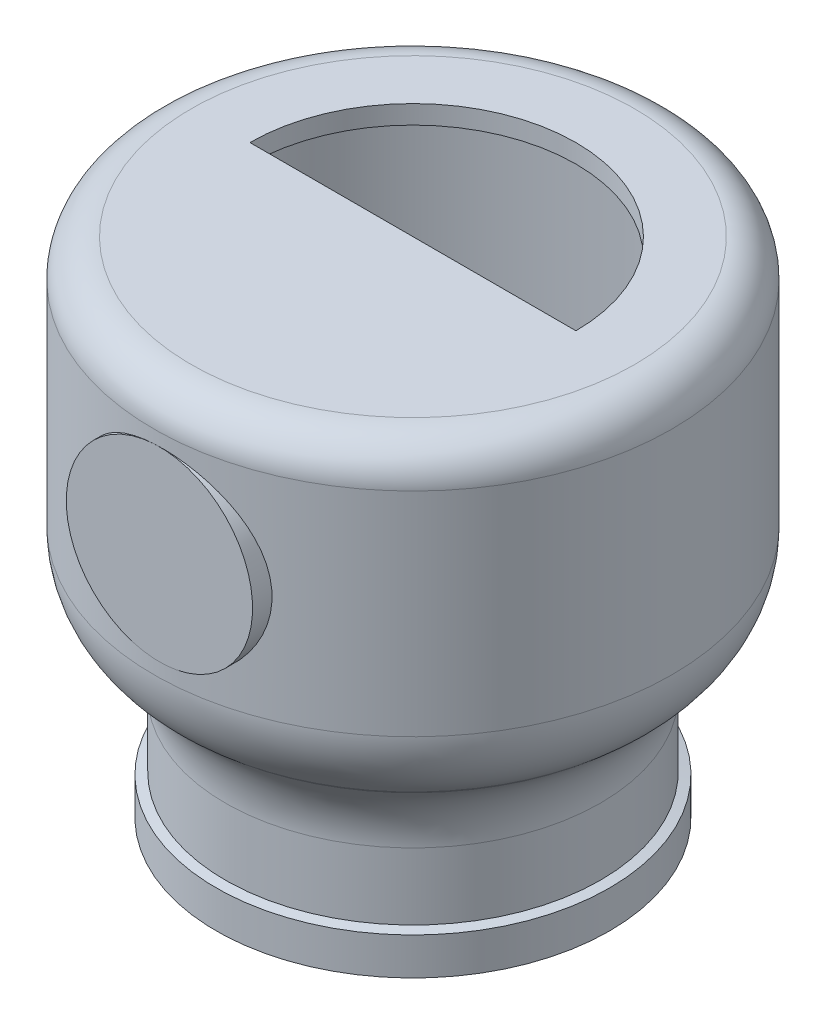
SolidWorks part; units mm, degrees
ref_plane "Front Plane" through (0, 0, 0) normal (0, 0, 1) x (1, 0, 0)
ref_plane "Top Plane" through (0, 0, 0) normal (0, 1, 0) x (1, 0, 0)
ref_plane "Right Plane" through (0, 0, 0) normal (1, 0, 0) x (0, 0, -1)
sketch "Sketch1" plane through (0, 0, 0) normal (0, 0, 1) x (1, 0, 0)
  line L0 (2.7649, 7.8218) -> (2.7649, 58.3592) construction
  line L1 (20.9, 0) -> (23.8716, 0)
  line L2 (23.8716, 0) -> (23.8716, 4)
  line L3 (23.8716, 4) -> (22.9, 4.2367)
  line L4 (22.9, 4.2367) -> (22.9, 11.4043)
  line L6 (20.9, 0) -> (20.9, 14)
  line L8 (2.7649, 52) -> (2.7649, 54)
  line L10 (17.2603, 17) -> (2.7649, 17)
  line L12 (19.9, 15) -> (2.7649, 15)
  line L13 (2.7649, 17) -> (2.7649, 15)
  line L15 (23.6882, 19.3396) -> (24.9883, 20.4305)
  line L16 (28.5604, 28.091) -> (28.5604, 50)
  line L17 (26.4721, 19.0648) -> (26.9883, 19.4979)
  line L18 (30.5604, 27.1583) -> (30.5604, 50)
  line L19 (26.5604, 52) -> (2.7649, 52)
  line L20 (26.5604, 54) -> (2.7649, 54)
  arc A0 (28.5604, 50) -> (26.5604, 52) centre (26.5604, 50) ccw
  arc A1 (30.5604, 50) -> (26.5604, 54) centre (26.5604, 50) ccw
  arc A2 (26.4721, 19.0648) -> (22.9, 11.4043) centre (32.9, 11.4043) ccw
  arc A3 (26.9883, 19.4979) -> (30.5604, 27.1583) centre (20.5604, 27.1583) ccw
  arc A4 (24.9883, 20.4305) -> (28.5604, 28.091) centre (18.5604, 28.091) ccw
  arc A5 (17.2603, 17) -> (23.6882, 19.3396) centre (17.2603, 27) ccw
  arc A6 (20.9, 14) -> (19.9, 15) centre (19.9, 14) ccw
  point P11 (22.9, 54)
  point P28 (28.5604, 23.4279)
  point P31 (20.9, 17)
  dimension "D8" = 2
  dimension "D9" = 4
  dimension "D4" = 2
  dimension "D16" = 10
  dimension "D17" = 10
  dimension "D18" = 10
  dimension "D19" = 1
  dimension "D1" = 2
  dimension "D2" = 4
  dimension "D3" = 1
  dimension "D5" = 140
  dimension "D6" = 2
  dimension "D7" = 2.9716
  dimension "D10" = 2
  dimension "D11" = 15
  dimension "D12" = 35
  dimension "D13" = 37
  dimension "D14" = 2
  dimension "D15" = 10
revolve "Revolve1" add sketch "Sketch1" angle 360 about L0
ref_plane "Plane1" through (0, 4, 0) normal (0, 1, 0) x (1, 0, 0)
sketch "Sketch3" plane through (0, 0, 0) normal (0, 0, 1) x (1, 0, 0)
  point P0 (1.2404, 19.1989)
ref_point "Point1"
ref_plane "Plane2" through (0, 0, 22.9) normal (0, 0, 1) x (1, 0, 0)
ref_plane "Plane3" through (0, 0, 27.7955) normal (0, 0, 1) x (1, 0, 0)
ref_plane "Plane4" through (0, 54, 0) normal (0, 1, 0) x (1, 0, 0)
sketch "Sketch9" plane through (0, 54, 0) normal (0, 1, 0) x (1, 0, 0)
  line L0 (-14.7351, -0.0013) -> (20.2649, -0.0013)
  arc A0 (20.2649, -0.0013) -> (-14.7351, -0.0013) centre (2.7649, -0.0013) ccw
  circle A1 centre (2.7649, 0) radius 17.1351 construction
  dimension "D1" = 35
  dimension "D3" = 17.5
  dimension "D2" = 17.5
extrude "Cut-Extrude2" cut sketch "Sketch9" against normal blind 40
sketch "Sketch10" plane through (0, 0, 27.7955) normal (0, 0, 1) x (1, 0, 0)
  line L0 (30.5604, 27.1583) -> (-25.0306, 27.1583) construction
  circle A0 centre (3.3463, 38.6583) radius 10
  dimension "D1" = 20
  dimension "D2" = 11.5
extrude "Boss-Extrude1" add sketch "Sketch10" against normal blind 5
